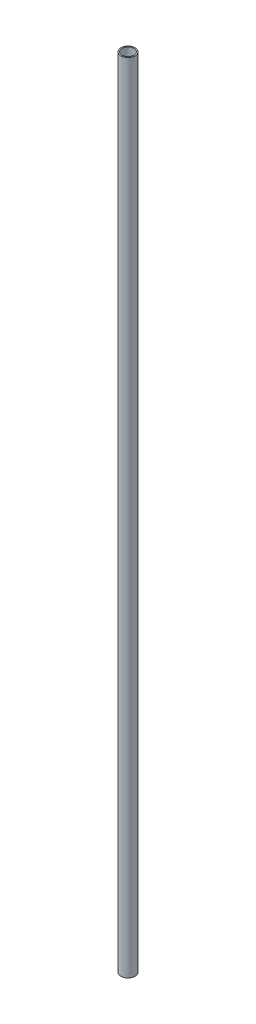
SolidWorks part; units mm, degrees
material "碳纤维"
ref_plane "前视基准面" through (0, 0, 0) normal (0, 0, 1) x (1, 0, 0)
ref_plane "上视基准面" through (0, 0, 0) normal (0, 1, 0) x (1, 0, 0)
ref_plane "右视基准面" through (0, 0, 0) normal (1, 0, 0) x (0, 0, -1)
sketch "草图1" plane through (0, 0, 0) normal (0, 1, 0) x (1, 0, 0)
  circle A0 centre (0, 0) radius 5
  circle A1 centre (0, 0) radius 6
  dimension "D1" = 10
  dimension "D2" = 12
extrude "凸台-拉伸1" add sketch "草图1" along normal blind 675
